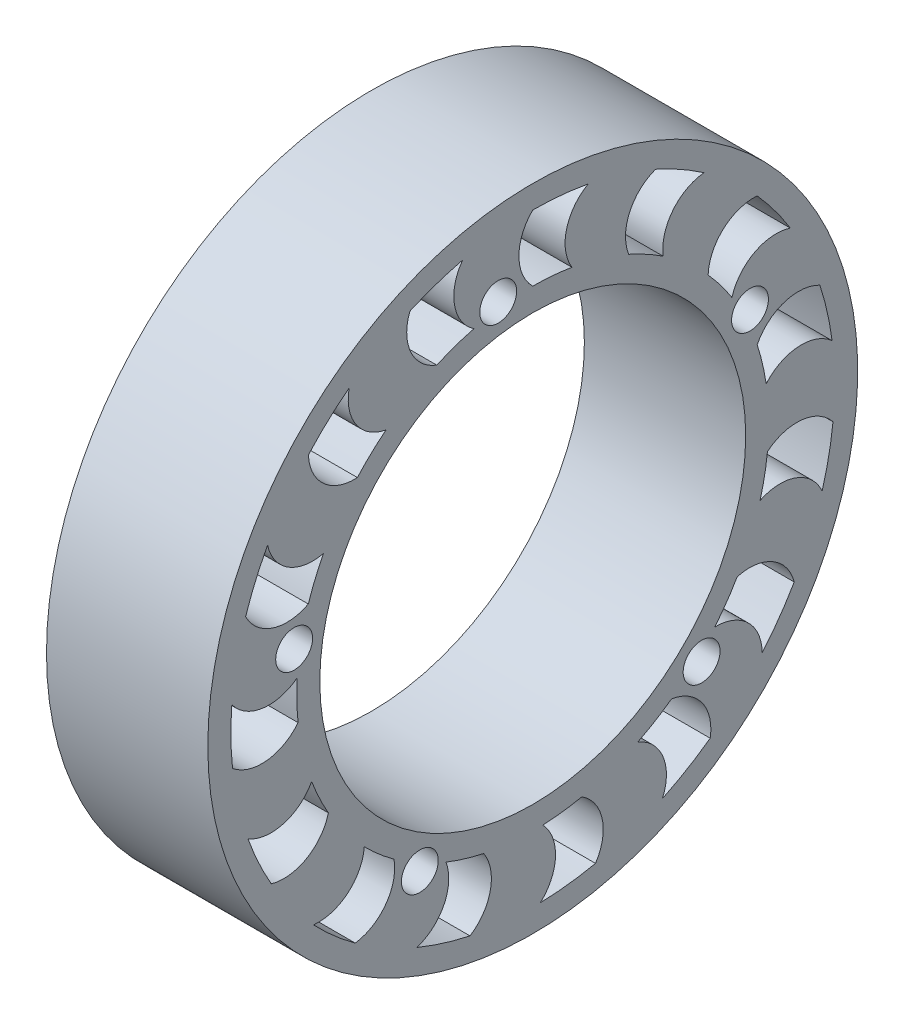
SolidWorks part; units mm, degrees
ref_plane "Front Plane" through (0, 0, 0) normal (0, 0, 1) x (1, 0, 0)
ref_plane "Top Plane" through (0, 0, 0) normal (0, 1, 0) x (1, 0, 0)
ref_plane "Right Plane" through (0, 0, 0) normal (1, 0, 0) x (0, 0, -1)
sketch "Sketch1" plane through (0, 0, 0) normal (0, 1, 0) x (1, 0, 0)
  line L0 (-17.5, 65.5) -> (17.5, 65.5)
  line L4 (17.5, 70.5) -> (-17.5, 70.5)
  line L5 (-17.5, 70.5) -> (-17.5, 65.5)
  line L6 (-1000, 0) -> (49000, 0) construction
  line L7 (17.5, 70.5) -> (17.5, 65.5)
  point P3 (0, 65.5)
  dimension "D1" = 35
  dimension "D2" = 5
  dimension "D4" = 141
revolve "Body" add sketch "Sketch1" angle 360 about L6
sketch "Sketch7" plane through (17.5, 0, 0) normal (-1, 0, 0) x (0, 0, 1)
  arc A1 (0, 65.5) -> (0, 51.2) centre (-6.9912, 58.35) cw
  circle A82 centre (0, 0) radius 46.2
  circle A83 centre (0, 0) radius 65.5 construction
  arc A84 (0, 65.5) -> (-12, 64.3914) centre (0, 0) ccw
  arc A85 (0, 51.2) -> (-8.5, 50.4895) centre (0, 0) ccw
  arc A88 (-12, 64.3914) -> (-8.5, 50.4895) centre (-17.0119, 55.738) cw
  arc A89 (26.6413, 59.8372) -> (20.8249, 46.7735) centre (17.3463, 56.149) cw
  circle A90 centre (0, 0) radius 51.2 construction
  arc A91 (26.6413, 59.8372) -> (15.2278, 63.7053) centre (0, 0) ccw
  arc A92 (20.8249, 46.7735) -> (12.7708, 49.5817) centre (0, 0) ccw
  arc A93 (15.2278, 63.7053) -> (12.7708, 49.5817) centre (7.1295, 57.8386) cw
  arc A94 (48.676, 43.8281) -> (38.049, 34.2595) centre (38.6844, 44.2393) cw
  arc A95 (48.676, 43.8281) -> (39.8226, 52.004) centre (0, 0) ccw
  arc A96 (38.049, 34.2595) -> (31.8334, 40.1008) centre (0, 0) ccw
  arc A97 (39.8226, 52.004) -> (31.8334, 40.1008) centre (30.0382, 49.9383) cw
  arc A98 (62.2942, 20.2406) -> (48.6941, 15.8217) centre (53.3337, 24.6802) cw
  arc A99 (62.2942, 20.2406) -> (57.5316, 31.3107) centre (0, 0) ccw
  arc A100 (48.6941, 15.8217) -> (45.3917, 23.6861) centre (0, 0) ccw
  arc A101 (57.5316, 31.3107) -> (45.3917, 23.6861) centre (47.753, 33.4033) cw
  arc A102 (65.1412, -6.8466) -> (50.9195, -5.3519) centre (58.7611, 0.8537) cw
  arc A103 (65.1412, -6.8466) -> (65.293, 5.2035) centre (0, 0) ccw
  arc A104 (50.9195, -5.3519) -> (51.1014, 3.1758) centre (0, 0) ccw
  arc A105 (65.293, 5.2035) -> (51.1014, 3.1758) centre (57.2109, 11.0925) cw
  arc A106 (56.7247, -32.75) -> (44.3405, -25.6) centre (54.0282, -23.1204) cw
  arc A107 (56.7247, -32.75) -> (61.7646, -21.8034) centre (0, 0) ccw
  arc A108 (44.3405, -25.6) -> (47.9752, -17.8835) centre (0, 0) ccw
  arc A109 (61.7646, -21.8034) -> (47.9752, -17.8835) centre (56.7765, -13.1362) cw
  arc A110 (38.4999, -52.9906) -> (30.0946, -41.4217) centre (39.9533, -43.0968) cw
  arc A111 (38.4999, -52.9906) -> (47.5565, -45.0403) centre (0, 0) ccw
  arc A112 (30.0946, -41.4217) -> (36.5536, -35.8507) centre (0, 0) ccw
  arc A113 (47.5565, -45.0403) -> (36.5536, -35.8507) centre (46.5249, -35.0936) cw
  arc A114 (13.6182, -64.0687) -> (10.6451, -50.0812) centre (18.9701, -55.6214) cw
  arc A115 (13.6182, -64.0687) -> (25.1255, -60.4893) centre (0, 0) ccw
  arc A116 (10.6451, -50.0812) -> (18.8116, -47.6189) centre (0, 0) ccw
  arc A117 (25.1255, -60.4893) -> (18.8116, -47.6189) centre (28.2288, -50.983) cw
  arc A118 (-13.6182, -64.0687) -> (-10.6451, -50.0812) centre (-5.2932, -58.5285) cw
  arc A119 (-13.6182, -64.0687) -> (-1.6499, -65.4792) centre (0, 0) ccw
  arc A120 (-10.6451, -50.0812) -> (-2.1831, -51.1534) centre (0, 0) ccw
  arc A121 (-1.6499, -65.4792) -> (-2.1831, -51.1534) centre (5.0516, -58.057) cw
  arc A122 (-38.4999, -52.9906) -> (-30.0946, -41.4217) centre (-28.6412, -51.3155) cw
  arc A123 (-38.4999, -52.9906) -> (-28.1401, -59.1471) centre (0, 0) ccw
  arc A124 (-30.0946, -41.4217) -> (-22.8003, -45.843) centre (0, 0) ccw
  arc A125 (-28.1401, -59.1471) -> (-22.8003, -45.843) centre (-18.999, -55.0924) cw
  arc A126 (-56.7247, -32.75) -> (-44.3405, -25.6) centre (-47.037, -35.2296) cw
  arc A127 (-56.7247, -32.75) -> (-49.7646, -42.588) centre (0, 0) ccw
  arc A128 (-44.3405, -25.6) -> (-39.4752, -32.606) centre (0, 0) ccw
  arc A129 (-49.7646, -42.588) -> (-39.4752, -32.606) centre (-39.7646, -42.6018) cw
  arc A130 (-65.1412, -6.8466) -> (-50.9195, -5.3519) centre (-57.2996, -13.0522) cw
  arc A131 (-65.1412, -6.8466) -> (-62.7843, -18.665) centre (0, 0) ccw
  arc A132 (-50.9195, -5.3519) -> (-49.3244, -13.731) centre (0, 0) ccw
  arc A133 (-62.7843, -18.665) -> (-49.3244, -13.731) centre (-53.6545, -22.7449) cw
  arc A134 (-62.2942, 20.2406) -> (-48.6941, 15.8217) centre (-57.6546, 11.3821) cw
  arc A135 (-62.2942, 20.2406) -> (-64.948, 8.4854) centre (0, 0) ccw
  arc A136 (-48.6941, 15.8217) -> (-50.645, 7.5181) centre (0, 0) ccw
  arc A137 (-64.948, 8.4854) -> (-50.645, 7.5181) centre (-58.267, 1.0447) cw
  arc A138 (-48.676, 43.8281) -> (-38.049, 34.2595) centre (-48.0406, 33.8483) cw
  arc A139 (-48.676, 43.8281) -> (-55.8817, 34.1685) centre (0, 0) ccw
  arc A140 (-38.049, 34.2595) -> (-43.2086, 27.4673) centre (0, 0) ccw
  arc A141 (-55.8817, 34.1685) -> (-43.2086, 27.4673) centre (-52.8046, 24.6537) cw
  arc A142 (-26.6413, 59.8372) -> (-20.8249, 46.7735) centre (-30.1199, 50.4618) cw
  arc A143 (-26.6413, 59.8372) -> (-37.1529, 53.9436) centre (0, 0) ccw
  arc A144 (-20.8249, 46.7735) -> (-28.3011, 42.6672) centre (0, 0) ccw
  arc A145 (-37.1529, 53.9436) -> (-28.3011, 42.6672) centre (-38.2119, 43.9998) cw
  point P5 (51.25, 0)
  point P99 (0, 0)
  dimension "D1" = 92.4
  dimension "D5" = 10
  dimension "D3" = 12
  dimension "D4" = 8.5
  dimension "D6" = 10
  dimension "D2" = 5
extrude "Reinforcement" add sketch "Sketch7" along normal up to surface (35 mm away)
sketch "Sketch8" plane through (-17.5, 0, 0) normal (-1, 0, 0) x (0, 0, 1)
  circle A0 centre (7.5, 52) radius 4
  circle A1 centre (51.7726, 8.936) radius 4
  circle A2 centre (24.4972, -46.4773) radius 4
  circle A3 centre (-36.6325, -37.6605) radius 4
  circle A4 centre (-47.1373, 23.2018) radius 4
  point P14 (0, 0)
  dimension "D1" = 8
  dimension "D2" = 7.5
  dimension "D3" = 52
extrude "Inserts_Holes_A" cut sketch "Sketch8" against normal blind 12.7
mirror "Mirror1" about plane through (0, 0, 0) normal (1, 0, 0) of "Inserts_Holes_A"
